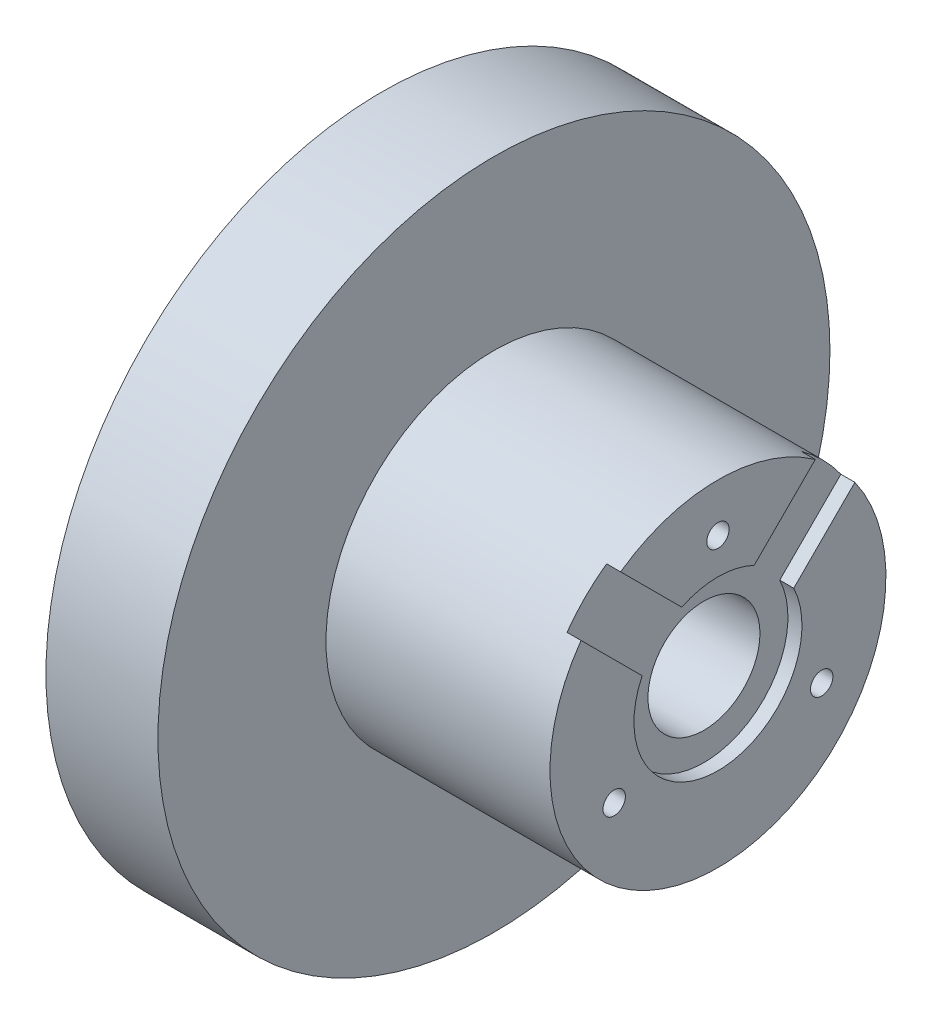
SolidWorks part; units mm, degrees
ref_plane "Front" through (0, 0, 0) normal (0, 0, 1) x (1, 0, 0)
ref_plane "Top" through (0, 0, 0) normal (0, 1, 0) x (1, 0, 0)
ref_plane "Right" through (0, 0, 0) normal (1, 0, 0) x (0, 0, -1)
sketch "Sketch1" plane through (0, 0, 0) normal (1, 0, 0) x (0, 0, -1)
  circle A0 centre (0, 0) radius 38.1
  dimension "D1" = 76.2
extrude "Boss-Extrude1" add sketch "Sketch1" along normal blind 12.7
sketch "Sketch2" plane through (12.7, 0, 0) normal (1, 0, 0) x (0, 0, -1)
  circle A0 centre (0, 0) radius 19.05
  dimension "D1" = 38.1
extrude "Boss-Extrude2" add sketch "Sketch2" along normal blind 25.4
sketch "Sketch3" plane through (38.1, 0, 0) normal (1, 0, 0) x (0, 0, -1)
  circle A0 centre (0, 0) radius 6.35
  dimension "D1" = 12.7
extrude "Cut-Extrude1" cut sketch "Sketch3" against normal through all
sketch "Sketch4" plane through (38.1, 0, 0) normal (1, 0, 0) x (0, 0, -1)
  line L0 (0, 0) -> (0, 19.05) construction
  circle A0 centre (0, 0) radius 19.05 construction
  circle A1 centre (0, 13.5835) radius 1.27
  circle A2 centre (11.7636, -6.7917) radius 1.27
  circle A3 centre (-11.7636, -6.7917) radius 1.27
  dimension "D1" = 2.54
  dimension "D2" = 3
extrude "Cut-Extrude2" cut sketch "Sketch4" against normal blind 6.35
sketch "Sketch5" plane through (38.1, 0, 0) normal (1, 0, 0) x (0, 0, -1)
  line L0 (0, 0) -> (-13.4704, 13.4704) construction
  line L1 (-15.7154, 11.2253) -> (-11.2253, 15.7154)
  line L2 (-2.2451, -2.2451) -> (2.2451, 2.2451)
  line L3 (-15.7154, 11.2253) -> (-2.2451, -2.2451)
  line L4 (-11.2253, 15.7154) -> (2.2451, 2.2451)
  line L5 (-19.05, 0) -> (19.05, 0) construction
  line L6 (15.7154, 11.2253) -> (2.2451, -2.2451)
  line L7 (-2.2451, 2.2451) -> (2.2451, -2.2451)
  line L8 (11.2253, 15.7154) -> (-2.2451, 2.2451)
  line L9 (11.2253, 15.7154) -> (15.7154, 11.2253)
  circle A0 centre (0, 0) radius 19.05 construction
  circle A1 centre (0, 0) radius 9.525
  point P8 (-13.4704, 13.4704)
  point P11 (0, 0)
  point P16 (0, 0)
  circle M10 centre (0, 0) radius 6.35
  circle M11 centre (0, 0) radius 19.05
  dimension "D4" = 19.05
  dimension "D1" = 6.35
  dimension "D2" = 45
  dimension "D3" = 2
extrude "Cut-Extrude3" cut sketch "Sketch5" against normal blind 1.5875 contours L1 L3 M11 | L4 L1 M11 | L4 L3 M11 M10 | L8 L6 M11 M10 | L9 L6 M11 | L9 L8 M11 | L3 A1 L6 M10 | L8 A1 L4 M10 | L4 A1 L3 M10 | L6 A1 L8 M10
